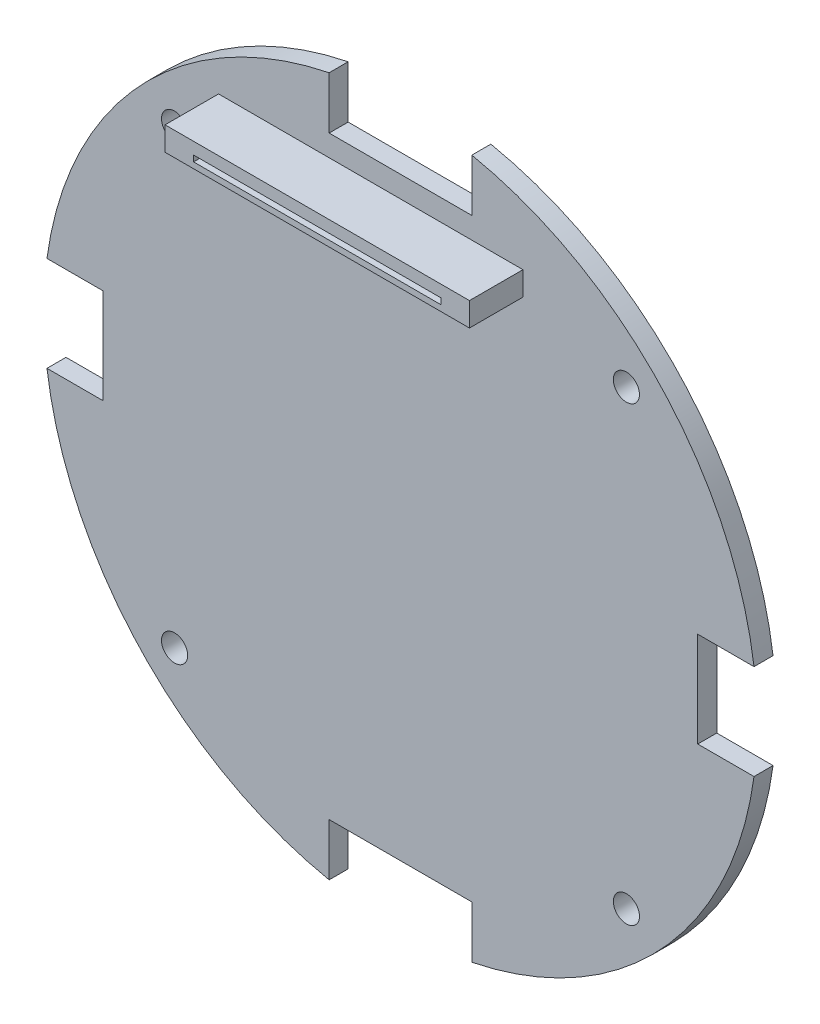
SolidWorks part; units mm, degrees
ref_plane "Front Plane" through (0, 0, 0) normal (0, 0, 1) x (1, 0, 0)
ref_plane "Top Plane" through (0, 0, 0) normal (0, 1, 0) x (1, 0, 0)
ref_plane "Right Plane" through (0, 0, 0) normal (1, 0, 0) x (0, 0, -1)
sketch "Sketch1" plane through (0, 0, 0) normal (0, 0, 1) x (1, 0, 0)
  line L0 (0, 36.6925) -> (0, -37.1692) construction
  line L1 (-31.6424, 0) -> (36.5285, 0) construction
  line L2 (-6, 29.3939) -> (-6, 25)
  line L3 (6, 29.3939) -> (6, 25)
  line L4 (-29.7321, 4) -> (-25, 4)
  line L5 (-29.7321, -4) -> (-25, -4)
  line L6 (-25, 4) -> (-25, -4)
  line L7 (-6, -25) -> (6, -25)
  line L8 (25, 4) -> (25, -4)
  line L9 (-6, 25) -> (6, 25)
  line L10 (-6, -25) -> (-6, -29.3939)
  line L12 (25, 4) -> (29.7321, 4)
  line L14 (25, -4) -> (29.7321, -4)
  line L15 (6, -25) -> (6, -29.3939)
  arc A0 (-6, 29.3939) -> (-29.7321, 4) centre (0, 0) ccw
  arc A1 (29.7321, 4) -> (6, 29.3939) centre (0, 0) ccw
  arc A2 (6, -29.3939) -> (29.7321, -4) centre (0, 0) ccw
  arc A3 (-29.7321, -4) -> (-6, -29.3939) centre (0, 0) ccw
  dimension "D1" = 60
  dimension "D2" = 8
  dimension "D3" = 50
  dimension "D4" = 50
  dimension "D5" = 12
extrude "Boss-Extrude1" add sketch "Sketch1" along normal blind 1.6
sketch "Sketch2" plane through (0, 0, 0) normal (0, 0, 1) x (1, 0, 0)
  line L0 (0, 16.6474) -> (0, -15.5188) construction
  line L1 (-19.4337, 0) -> (16.5416, 0) construction
  circle A0 centre (-19, 19) radius 1.1
  circle A1 centre (19, 19) radius 1.1
  circle A2 centre (19, -19) radius 1.1
  circle A3 centre (-19, -19) radius 1.1
  dimension "D1" = 2.2
  dimension "D2" = 38
  dimension "D3" = 38
extrude "Cut-Extrude1" cut sketch "Sketch2" along normal through all
sketch "Sketch3" plane through (0, 0, 1.6) normal (0, 0, 1) x (1, 0, 0)
  line L0 (-15.3, 21.2) -> (10.3, 23.2) construction
  line L1 (-15.3, 23.2) -> (10.3, 23.2)
  line L2 (-15.3, 23.2) -> (-15.3, 21.2)
  line L3 (-15.3, 21.2) -> (10.3, 21.2)
  line L4 (10.3, 23.2) -> (10.3, 21.2)
  point P5 (-2.5, 22.2)
  dimension "D1" = 22.2
  dimension "D2" = 2
  dimension "D3" = 2.5
  dimension "D4" = 25.6
extrude "Boss-Extrude2" add sketch "Sketch3" along normal blind 4.5
sketch "Sketch4" plane through (0, 0, 6.1) normal (0, 0, 1) x (1, 0, 0)
  line L0 (10.3, 23.2) -> (-15.3, 23.2) construction
  line L1 (-12.9, 22.2) -> (7.9, 22.2)
  line L2 (-12.9, 22.2) -> (-12.9, 21.7)
  line L3 (-12.9, 21.7) -> (7.9, 21.7)
  line L4 (7.9, 22.2) -> (7.9, 21.7)
  point P4 (-2.5, 23.2)
  point P5 (-2.5, 22.2)
  dimension "D1" = 20.8
  dimension "D2" = 0.5
  dimension "D3" = 1
extrude "Cut-Extrude2" cut sketch "Sketch4" against normal blind 2
sketch "Sketch5" plane through (0, 0, 0) normal (0, 0, -1) x (-1, 0, 0)
  line L0 (-4.9, 4.79) -> (-8.6, -12.41) construction
  line L1 (-8.6, 4.79) -> (-4.9, 4.79)
  line L2 (-8.6, 4.79) -> (-8.6, -12.41)
  line L3 (-8.6, -12.41) -> (-4.9, -12.41)
  line L4 (-4.9, 4.79) -> (-4.9, -12.41)
  line L5 (2.09, -6.89) -> (5.79, -6.89)
  line L6 (2.09, -6.89) -> (2.09, -23.59)
  line L7 (2.09, -23.59) -> (5.79, -23.59)
  line L8 (5.79, -6.89) -> (5.79, -23.59)
  line L9 (5.79, -6.89) -> (2.09, -23.59) construction
  point P8 (-6.75, -3.81)
  point P9 (3.94, -15.24)
  dimension "D1" = 3.7
  dimension "D2" = 6.75
  dimension "D3" = 3.81
  dimension "D4" = 3.94
  dimension "D5" = 15.24
  dimension "D6" = 17.2
  dimension "D7" = 16.7
extrude "Boss-Extrude3" add sketch "Sketch5" along normal blind 4.5
equation "\"D7@Sketch5\"=17.2-0.5"
